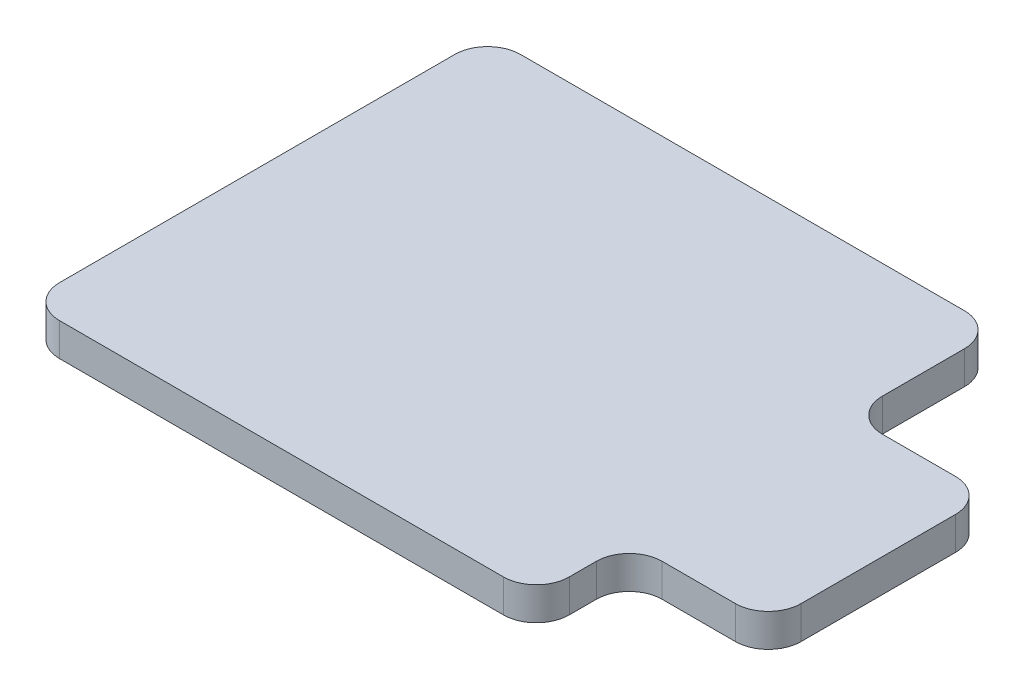
SolidWorks part; units mm, degrees
ref_plane "Front Plane" through (0, 0, 0) normal (0, 0, 1) x (1, 0, 0)
ref_plane "Top Plane" through (0, 0, 0) normal (0, 1, 0) x (1, 0, 0)
ref_plane "Right Plane" through (0, 0, 0) normal (1, 0, 0) x (0, 0, -1)
sketch "Sketch1" plane through (0, 0, 0) normal (0, 1, 0) x (1, 0, 0)
  line L0 (19.6582, 8.907) -> (19.6582, 15.24)
  line L1 (-17.1182, -17.78) -> (17.1182, -17.78)
  line L2 (-19.6582, -15.24) -> (-19.6582, 15.24)
  line L3 (-17.1182, 17.78) -> (17.1182, 17.78)
  line L4 (19.6582, -15.24) -> (19.6582, -13.1559)
  line L5 (-19.6582, -17.78) -> (19.6582, 17.78) construction
  line L6 (-19.6582, 17.78) -> (19.6582, -17.78) construction
  line L7 (22.1982, 6.367) -> (27.8398, 6.367)
  line L9 (22.1982, -10.6159) -> (27.8398, -10.6159)
  line L10 (30.3798, 3.827) -> (30.3798, -8.0759)
  arc A0 (-17.1182, -17.78) -> (-19.6582, -15.24) centre (-17.1182, -15.24) cw
  arc A1 (-19.6582, 15.24) -> (-17.1182, 17.78) centre (-17.1182, 15.24) cw
  arc A2 (17.1182, -17.78) -> (19.6582, -15.24) centre (17.1182, -15.24) ccw
  arc A3 (27.8398, -10.6159) -> (30.3798, -8.0759) centre (27.8398, -8.0759) ccw
  arc A4 (27.8398, 6.367) -> (30.3798, 3.827) centre (27.8398, 3.827) cw
  arc A5 (17.1182, 17.78) -> (19.6582, 15.24) centre (17.1182, 15.24) cw
  arc A6 (19.6582, -13.1559) -> (22.1982, -10.6159) centre (22.1982, -13.1559) cw
  arc A7 (22.1982, 6.367) -> (19.6582, 8.907) centre (22.1982, 8.907) cw
  point P0 (0, 0)
  point P30 (19.6582, 6.367)
  dimension "D1" = 2.54
  dimension "D2" = 2.54
  dimension "D3" = 35.56
  dimension "D4" = 50.038
extrude "Boss-Extrude1" add sketch "Sketch1" along normal blind 2.54 contours L1 L4 L3 L2 | L10 L7 L4 L9
